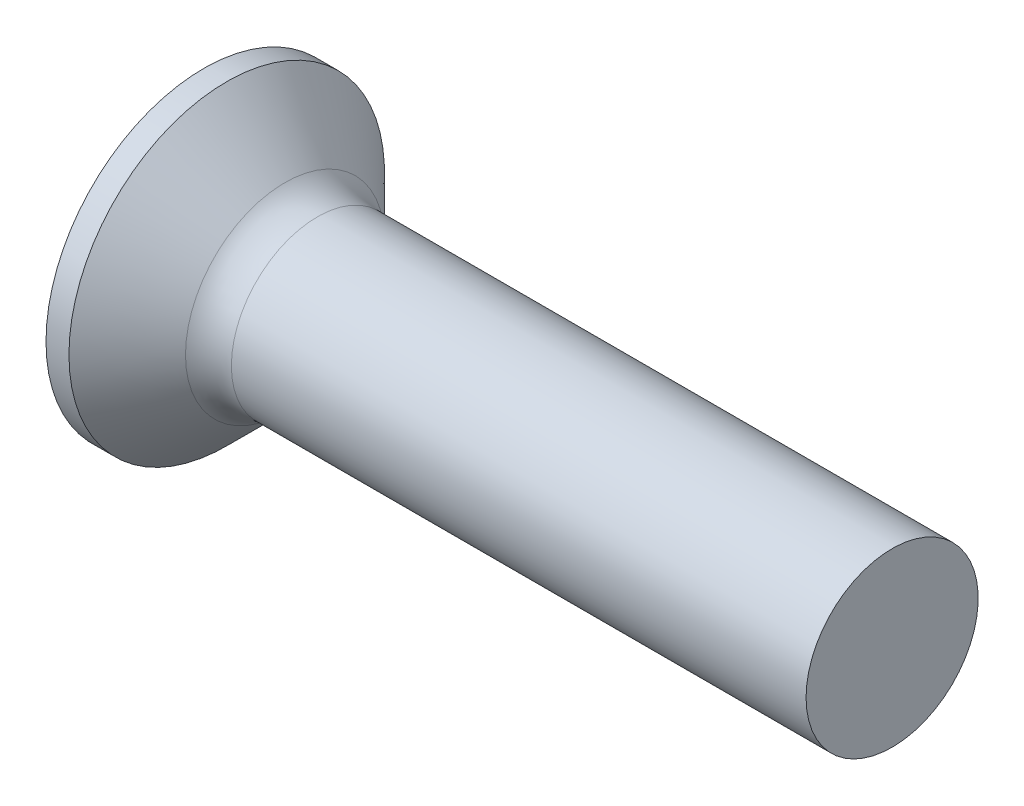
SolidWorks part; units mm, degrees
revolve "Base-Revolve" add sketch "BodySke" angle 360 about L5
sketch "BodySke" plane through (0, 0, 0) normal (0, 0, 1) x (1, 0, 0)
  line L0 (0, 0) -> (0, 2.75)
  line L1 (0, 2.75) -> (0.4, 2.75)
  line L2 (1.65, 1.5) -> (12, 1.5)
  line L3 (12, 1.5) -> (12, 0)
  line L4 (12, 0) -> (0, 0)
  line L5 (-6.35, 0) -> (82.55, 0) construction
  line L6 (1.65, -1.5) -> (12, -1.5) construction
  line L7 (0.4, -2.75) -> (1.65, -1.5) construction
  line L8 (0.4, 2.75) -> (1.65, 1.5)
  line L9 (0, -2.75) -> (0.4, -2.75) construction
  line L10 (2.15, 3.0875) -> (2.15, -6.4375) construction
  line L11 (0, 6.35) -> (0, -3.175) construction
  dimension "Diameter" = 3
  dimension "Length" = 12
  dimension "Head_ht" = 1.65
  dimension "Head_dia" = 5.5
  dimension "Head_ang" = 90
  dimension "D6" = 0.4
  dimension "Advance" = 0.5
  dimension "Thread_nom" = 12
cosmetic thread "ThreadCosmetic" [suppressed] parameters "Thread_length"=9.85, "Thread_minor"=2.439
ref_plane "Plane1" through (0, 0, 0) normal (0, 0, 1) x (1, 0, 0)
ref_plane "Plane2" through (0, 0, 0) normal (0, 1, 0) x (1, 0, 0)
ref_plane "Plane3" through (0, 0, 0) normal (1, 0, 0) x (0, 0, -1)
fillet "Fillet1" radius 0.8 1 edges at (1.65, 0, 1.5)
sketch "Sketch3" plane through (0, 0, 0) normal (-1, 0, 0) x (0, 0, 1)
  line L0 (-0.37, 1.5) -> (0.37, 1.5)
  line L1 (0.37, 1.5) -> (0.37, -1.5)
  line L2 (0.37, -1.5) -> (-0.37, -1.5)
  line L3 (-0.37, -1.5) -> (-0.37, 1.5)
  dimension "Cross_dia" = 3
  dimension "Cross_width" = 0.74
  dimension "D1" = 1.5
  dimension "D2" = 0.37
ref_plane "Plane4" through (2.01, 0, 0) normal (-1, 0, 0) x (0, 0, 1)
sketch "Sketch4" plane through (2.01, 0, 0) normal (-1, 0, 0) x (0, 0, 1)
  line L0 (-0.37, 0.4979) -> (0.37, 0.4979)
  line L3 (0.37, 0.4979) -> (0.37, -0.4979)
  line L4 (0.37, -0.4979) -> (-0.37, -0.4979)
  line L5 (-0.37, -0.4979) -> (-0.37, 0.4979)
  dimension "D2" = 0.9957
  dimension "D1" = 0.74
  dimension "D4" = 0.4979
  dimension "D3" = 0.37
loft "Recess" cut profiles "Sketch3", "Sketch4"
pattern_circular "RecPat" count 2 every 90 about axis through (0, 0, 0) along (1, 0, 0) of "Recess"
sketch "RecCorSke" plane through (0, 0, 0) normal (0, 0, 1) x (1, 0, 0)
  line L0 (-3.175, 0) -> (15.875, 0) construction
  line L2 (0, 0) -> (0, 0.6966)
  line L3 (0, 0.6966) -> (2.01, 0.556)
  line L4 (2.01, 0.556) -> (2.1907, 0)
  line L5 (2.1907, 0) -> (0, 0)
  dimension "Diameter" = 1.112
  dimension "Depth" = 2.01
  dimension "Draft_angle" = 4
  dimension "Bottom_angle" = 18
revolve "RecessCore" cut sketch "RecCorSke" angle 360 about L0
sketch "ThdSchSke" plane through (0, 0, 0) normal (0, 0, 1) x (1, 0, 0)
  line L0 (2.15, -1.2195) -> (1.9536, -1.5)
  line L1 (2.15, -1.2195) -> (2.3464, -1.5)
  line L2 (2.3464, -1.5) -> (2.3464, -1.875)
  line L3 (-3.175, 0) -> (5.1513, 0) construction
  line L5 (2.3464, -1.875) -> (1.9536, -1.875)
  line L6 (1.9536, -1.875) -> (1.9536, -1.5)
  line L7 (0, 2.75) -> (0, -2.75) construction
  dimension "Diameter" = 3
  dimension "Thread_minor" = 2.439
  dimension "Start" = 2.15
revolve "ThreadSchematic" [suppressed] cut sketch "ThdSchSke" angle 360 about L3
pattern_linear "ThdSchPat" [suppressed]
equation "\"D1@Sketch3\" = \"Cross_dia@Sketch3\" / 2"
equation "\"D2@Sketch3\" = \"Cross_width@Sketch3\" / 2"
equation "\"Depth@RecCorSke\" = \"Cross_depth@Plane4\""
equation "\"D1@Sketch4\" = \"Cross_width@Sketch3\""
equation "\"D2@Sketch4\" = \"Cross_dia@Sketch3\" - 2.0 * \"Cross_depth@Plane4\" * tan(26.5  * 0.017453292)"
equation "\"D3@Sketch4\" = \"D1@Sketch4\" / 2"
equation "\"D4@Sketch4\" = \"D2@Sketch4\" / 2"
equation "\"Thread_length@ThreadCosmetic\" = ((sgn( (\"Length@BodySke\" - \"Advance@BodySke\" * 1.0 - \"Head_ht@BodySke\" ) - \"Thread_nom@BodySke\" )-1)*( (\"Length@BodySke\" - \"Advance@BodySke\" * 1.0 - \"Head_ht@BodySke\" ) - \"Thread_nom@BodySke\" ))/-2+ \"Thread_nom@BodySke\""
equation "\"Thread_minor@ThdSchSke\" = \"Thread_minor@ThreadCosmetic\""
equation "\"Diameter@ThdSchSke\" = \"Diameter@BodySke\""
equation "\"Overcut@ThdSchSke\" = \"Diameter@BodySke\" * 1.25"
equation "\"Start@ThdSchSke\" = 0.000001 + \"Length@BodySke\" - \"Thread_length@ThreadCosmetic\"  '---Countersunk---"
equation "\"Num_threads@ThdSchPat\" = int( \"Thread_length@ThreadCosmetic\" / \"Advance@BodySke\" + 0.999 )  + 1"
equation "\"Advance@ThdSchPat\" = \"Thread_length@ThreadCosmetic\" /  (\"Num_threads@ThdSchPat\" - 1) 'relax it"
